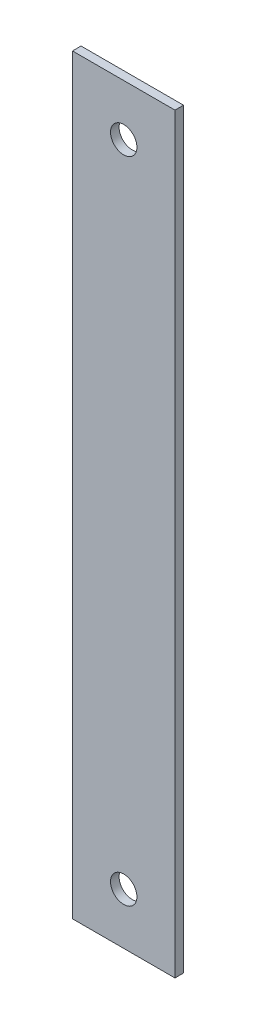
SolidWorks part; units mm, degrees
material "Plain Carbon Steel"
ref_plane "Front Plane" through (0, 0, 0) normal (0, 0, 1) x (1, 0, 0)
ref_plane "Top Plane" through (0, 0, 0) normal (0, 1, 0) x (1, 0, 0)
ref_plane "Right Plane" through (0, 0, 0) normal (1, 0, 0) x (0, 0, -1)
sketch "Sketch1" plane through (0, 0, 0) normal (0, 0, 1) x (1, 0, 0)
  line L1 (0, 0) -> (38.1, 0)
  line L2 (0, 0) -> (0, 279.4)
  line L3 (0, 279.4) -> (38.1, 279.4)
  line L4 (38.1, 0) -> (38.1, 279.4)
  dimension "D1" = 38.1
  dimension "D2" = 279.4
extrude "Boss-Extrude1" add sketch "Sketch1" along normal blind 3.175
hole_wizard "W (0.386) Diameter Hole1" positions "Sketch3" profile "Sketch2" hole size "W" standard "ANSI Inch" end condition through all
sketch "Sketch3" plane through (0, 0, 3.175) normal (0, 0, 1) x (1, 0, 0)
  line L0 (19.05, 0) -> (19.05, 19.05) construction
  line L1 (0, 0) -> (38.1, 0) construction
  line L2 (19.05, 19.05) -> (19.05, 260.35) construction
  line L3 (19.05, 260.35) -> (19.05, 279.4) construction
  line L4 (38.1, 279.4) -> (0, 279.4) construction
  point P0 (19.05, 260.35)
  point P2 (19.05, 19.05)
  dimension "D1" = 19.05
sketch "Sketch2" plane through (19.05, 260.35, 3.175) normal (1, 0, 0) x (0, -1, 0)
  line L0 (0, 0) -> (0, 3.175)
  line L1 (0, 3.175) -> (4.9022, 3.175)
  line L2 (4.9022, 3.175) -> (4.9022, 0)
  line L5 (4.9022, 0) -> (0, 0)
  line L11 (0, -6.35) -> (0, 107.95) construction
  dimension "Thru Hole Dia." = 9.8044
  dimension "Thru Hole Depth" = 3.175
